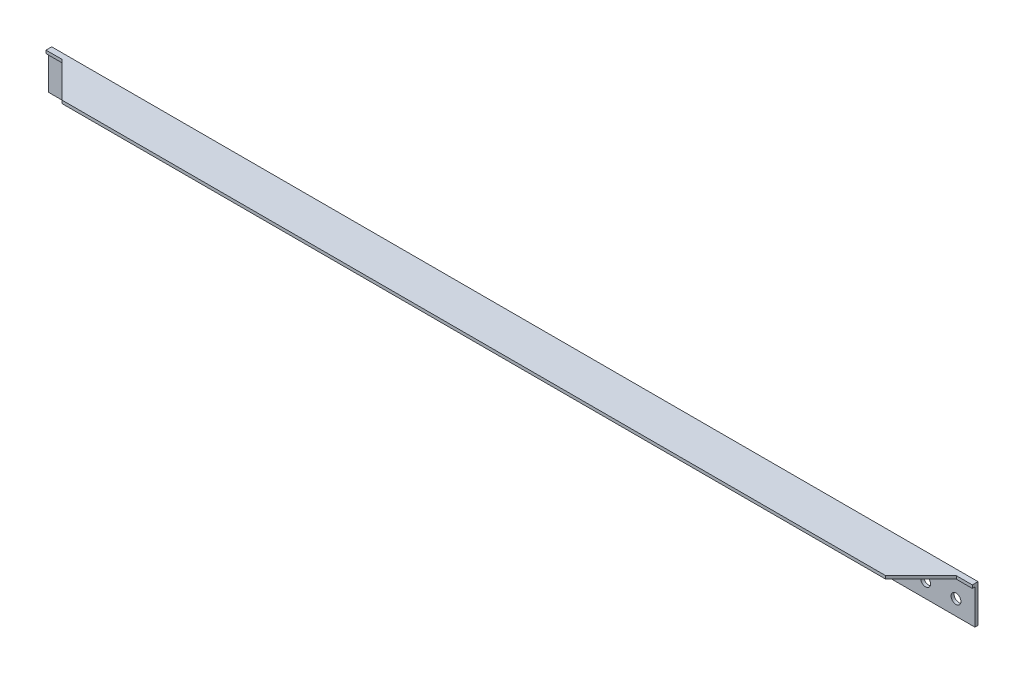
SolidWorks part; units mm, degrees
ref_plane "前视" through (0, 0, 0) normal (0, 0, 1) x (1, 0, 0)
ref_plane "上视" through (0, 0, 0) normal (0, 1, 0) x (1, 0, 0)
ref_plane "右视" through (0, 0, 0) normal (1, 0, 0) x (0, 0, -1)
sketch "草图1" plane through (0, 0, 0) normal (0, 0, 1) x (1, 0, 0)
  line L0 (0, 0) -> (0, 1201.1794) construction
  line L1 (-1220, 0) -> (1220, 0)
  line L2 (-1220, 0) -> (-1220, 100)
  line L3 (-1220, 100) -> (1220, 100)
  line L4 (1220, 0) -> (1220, 100)
  line L5 (1238.3745, 40) -> (698.9756, 40) construction
  line L6 (692.2249, 40) -> (138.717, 40) construction
  line L7 (0, 0) -> (804.1445, 0) construction
  line L8 (1170, -74.0451) -> (1170, 582.7434) construction
  line L9 (160, 72.6209) -> (160, 40) construction
  line L10 (1090, -107.6037) -> (1090, 582.7434) construction
  line L11 (1414, 542.8394) -> (1414, -805.3158) construction
  line L12 (138.717, 40) -> (-430.5746, 40) construction
  line L13 (-1414, 582.7434) -> (-1414, -1649.9569) construction
  circle A0 centre (1090, 40) radius 13
  circle A1 centre (1170, 40) radius 13
  circle A2 centre (-1170, 40) radius 13
  circle A3 centre (-1090, 40) radius 13
  circle A4 centre (0, 40) radius 13
  circle A5 centre (80, 40) radius 13
  circle A6 centre (160, 40) radius 13
  circle A7 centre (-160, 40) radius 13
  circle A8 centre (-80, 40) radius 13
  dimension "D4" = 50
  dimension "D5" = 80
  dimension "D8" = 80
  dimension "D6" = 26
  dimension "D1" = 2440
  dimension "D2" = 100
  dimension "D3" = 40
  dimension "D7" = 80
  dimension "D9" = 244
  dimension "D10" = 244
extrude "基体-拉伸" add sketch "草图1" along normal blind 8
sketch "草图2" plane through (0, 0, 8) normal (0, 0, 1) x (1, 0, 0)
  line L0 (1220, 0) -> (1220, 100) construction
  line L1 (-1220, 100) -> (1220, 100)
  line L2 (-1220, 100) -> (-1220, 92)
  line L3 (-1220, 92) -> (1220, 92)
  line L4 (1220, 100) -> (1220, 92)
  dimension "D1" = 8
extrude "凸台-拉伸1" add sketch "草图2" along normal blind 100
sketch "草图3" plane through (0, 100, 0) normal (0, 1, 0) x (-1, 0, 0)
  line L2 (-1220, 108) -> (-1220, 0) construction
  line L3 (-1220, 0) -> (1220, 0) construction
  line L4 (-1220, 108) -> (1220, 108) construction
  line L5 (-1085, 108) -> (-1178, 15)
  line L6 (-1085, 108) -> (-1220, 108)
  line L7 (-1220, 108) -> (-1220, 15)
  line L8 (-1220, 15) -> (-1178, 15)
  line L9 (0, 868.9044) -> (0, -812.8803) construction
  line L10 (1220, 108) -> (1220, 0) construction
  line L11 (1220, 15) -> (1178, 15)
  line L12 (1220, 108) -> (1220, 15)
  line L13 (1085, 108) -> (1220, 108)
  line L14 (1085, 108) -> (1178, 15)
  point P0 (-1220, 15)
  point P5 (-1085, 108)
  dimension "D1" = 15
  dimension "D2" = 135
  dimension "D3" = 45
extrude "切除-拉伸1" cut sketch "草图3" against normal through all
